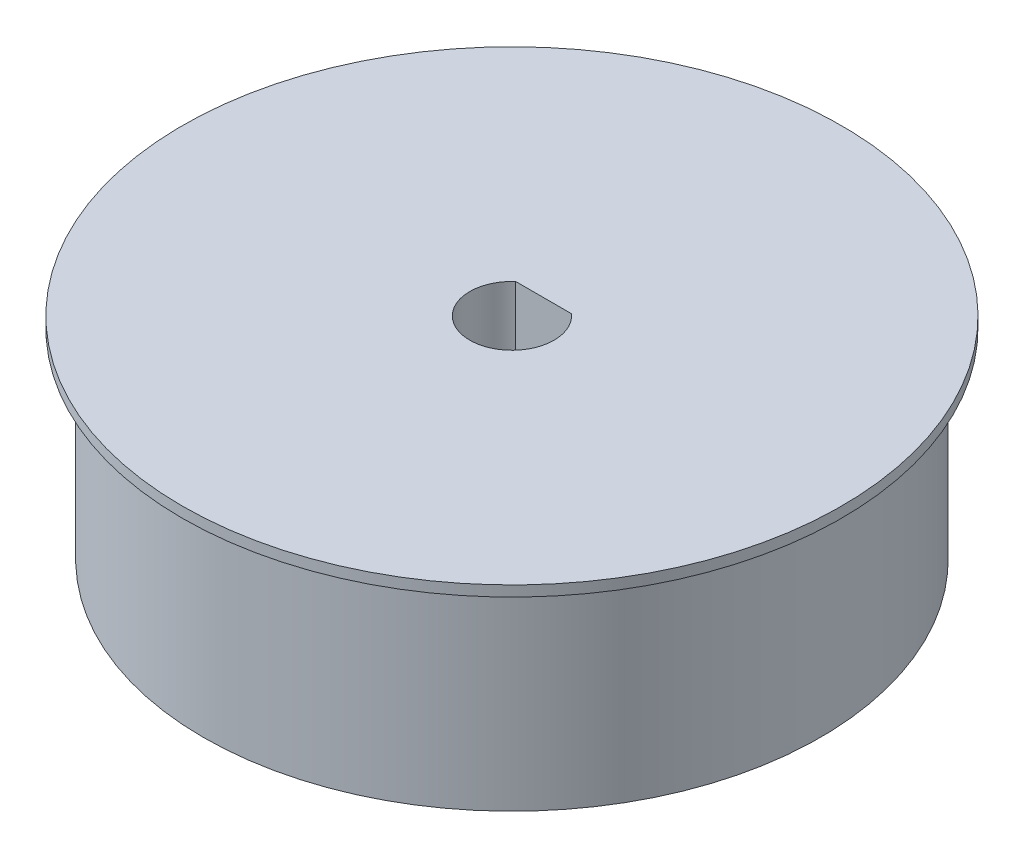
SolidWorks part; units mm, degrees
ref_plane "Front Plane" through (0, 0, 0) normal (0, 0, 1) x (1, 0, 0)
ref_plane "Top Plane" through (0, 0, 0) normal (0, 1, 0) x (1, 0, 0)
ref_plane "Right Plane" through (0, 0, 0) normal (1, 0, 0) x (0, 0, -1)
sketch "Sketch1" plane through (0, 0, 0) normal (0, 1, 0) x (1, 0, 0)
  line L0 (-1.3229, 1.5) -> (1.3229, 1.5)
  arc A0 (-1.3229, 1.5) -> (1.3229, 1.5) centre (0, 0) ccw
  circle A1 centre (0, 0) radius 14.625
  dimension "D1" = 29.25
  dimension "D2" = 4
  dimension "D3" = 1.5
extrude "Boss-Extrude1" add sketch "Sketch1" along normal blind 10
sketch "Sketch2" plane through (0, 10, 0) normal (0, 1, 0) x (1, 0, 0)
  line L0 (-1.3229, 1.5) -> (1.3229, 1.5)
  circle A0 centre (0, 0) radius 15.625
  circle A1 centre (0, 0) radius 14.625 construction
  circle A2 centre (0, 0) radius 2 construction
  arc A3 (-1.3229, 1.5) -> (1.3229, 1.5) centre (0, 0) ccw
  point P10 (0, 1.5)
  dimension "D1" = 1
  dimension "D2" = 1.5
extrude "Boss-Extrude2" add sketch "Sketch2" against normal blind 0.5
